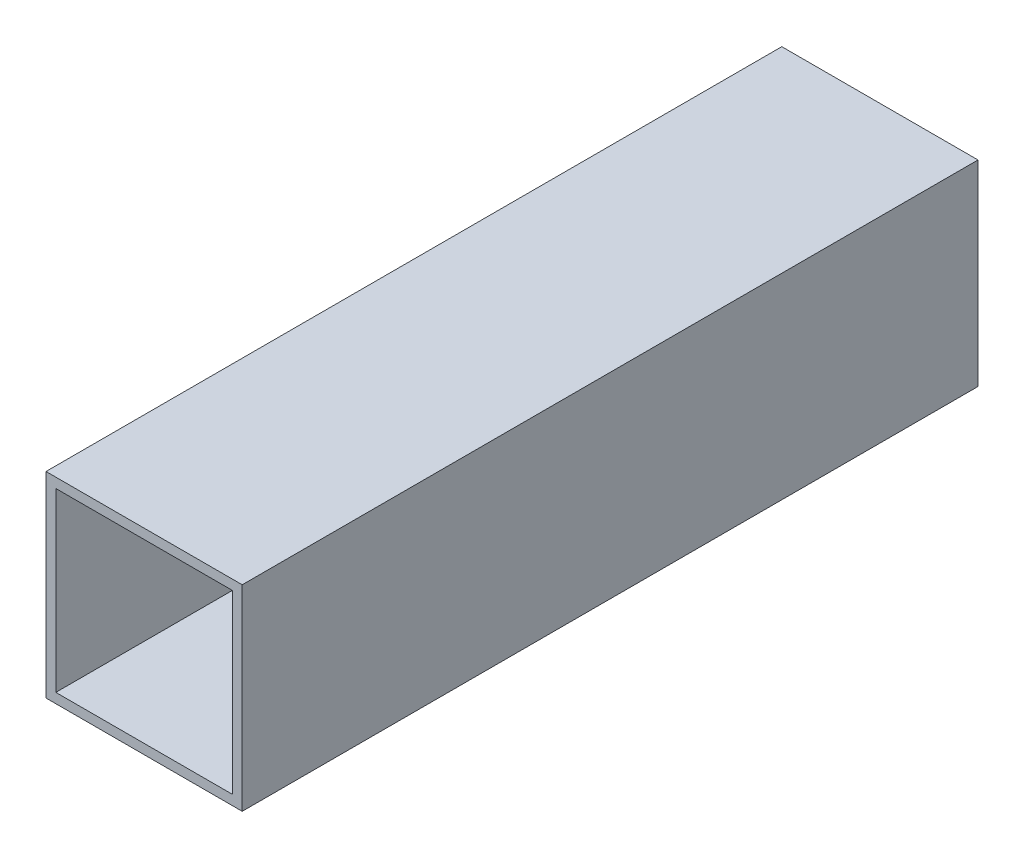
SolidWorks part; units mm, degrees
material "Труба 80х80х4,0 ГОСТ 8639-82 / В 10 ГОСТ 13663-86"
ref_plane "Спереди" through (0, 0, 0) normal (0, 0, 1) x (1, 0, 0)
ref_plane "Сверху" through (0, 0, 0) normal (0, 1, 0) x (1, 0, 0)
ref_plane "Справа" through (0, 0, 0) normal (1, 0, 0) x (0, 0, -1)
sketch "Эскиз1" plane through (0, 0, 0) normal (0, 0, 1) x (1, 0, 0)
  line L1 (-40, -40) -> (40, -40)
  line L2 (-40, -40) -> (-40, 40)
  line L3 (-40, 40) -> (40, 40)
  line L4 (40, -40) -> (40, 40)
  line L6 (-36, -36) -> (36, -36)
  line L7 (-36, -36) -> (-36, 36)
  line L8 (-36, 36) -> (36, 36)
  line L9 (36, -36) -> (36, 36)
extrude "Бобышка-Вытянуть1" add sketch "Эскиз1" along normal blind 300
